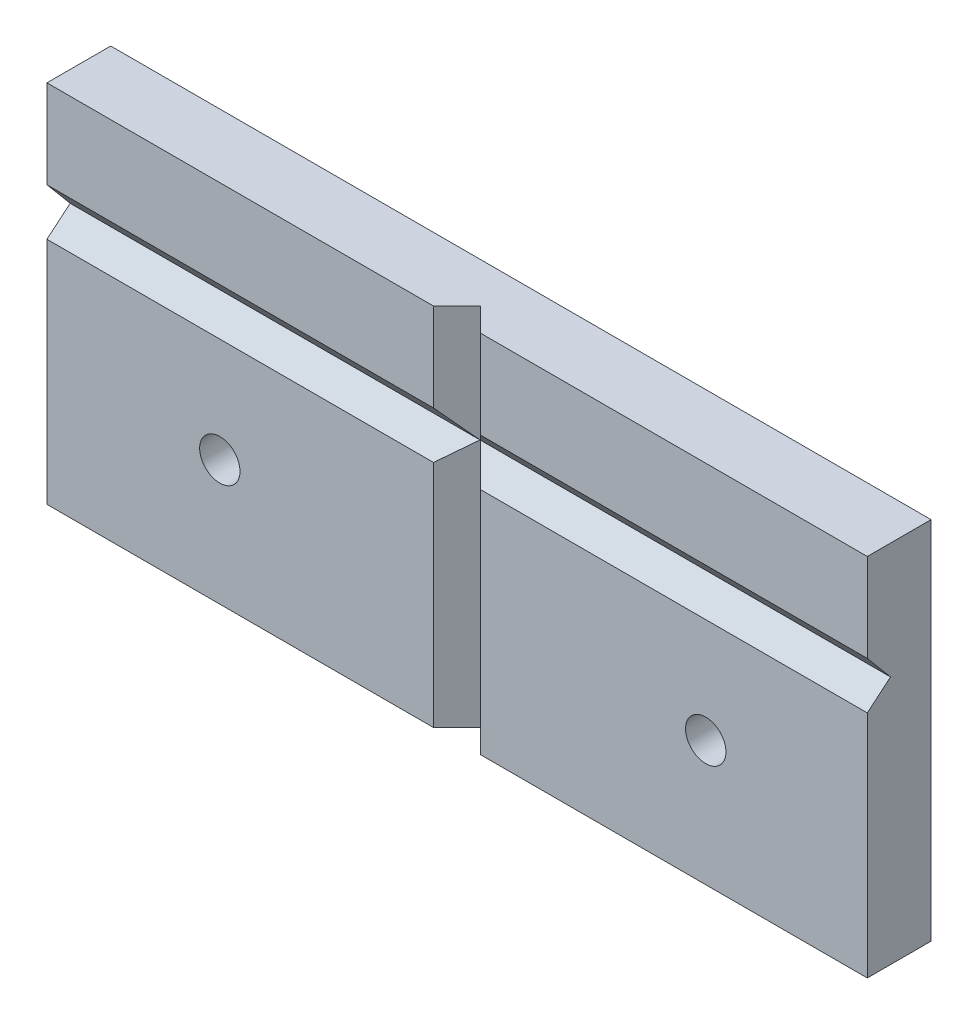
SolidWorks part; units mm, degrees
ref_plane "Front Plane" through (0, 0, 0) normal (0, 0, 1) x (1, 0, 0)
ref_plane "Top Plane" through (0, 0, 0) normal (0, 1, 0) x (1, 0, 0)
ref_plane "Right Plane" through (0, 0, 0) normal (1, 0, 0) x (0, 0, -1)
sketch "Sketch1" plane through (0, 0, 0) normal (0, 0, 1) x (1, 0, 0)
  line L6 (-101.6, 83.312) -> (-101.6, 38.1)
  line L7 (-101.6, 38.1) -> (-69.85, 38.1)
  line L8 (-69.85, 38.1) -> (-31.75, 38.1)
  line L9 (-31.75, 38.1) -> (0, 38.1)
  line L10 (0, 38.1) -> (0, 83.312)
  line L11 (0, 83.312) -> (-101.6, 83.312)
  line L12 (-101.6, 83.312) -> (-101.6, 38.1)
  line L13 (-101.6, 38.1) -> (-69.85, 38.1)
  line L14 (-69.85, 38.1) -> (-31.75, 38.1)
  line L15 (-31.75, 38.1) -> (0, 38.1)
  line L16 (0, 38.1) -> (0, 83.312)
  line L17 (0, 83.312) -> (-101.6, 83.312)
  dimension "D1" = 0
extrude "Boss-Extrude1" add sketch "Sketch1" along normal blind 7.8994
sketch "Sketch2" plane through (-101.6, 0, 0) normal (-1, 0, 0) x (0, 0, 1)
  line L0 (7.8994, 72.3762) -> (5.0225, 68.9498)
  line L1 (7.8994, 83.312) -> (7.8994, 38.1) construction
  line L2 (5.0225, 68.9498) -> (7.8994, 66.5342)
  dimension "D1" = 5.842
extrude "Cut-Extrude1" cut sketch "Sketch2" against normal through all and the other way through all
sketch "Sketch3" plane through (0, 83.312, 0) normal (0, 1, 0) x (1, 0, 0)
  line L0 (-47.879, -7.8994) -> (-50.8, -4.9784)
  line L1 (0, -7.8994) -> (-101.6, -7.8994) construction
  line L2 (-50.8, -4.9784) -> (-53.721, -7.8994)
  line L3 (-50.8, -7.8994) -> (-50.8, 0) construction
  line L4 (0, 0) -> (-101.6, 0) construction
  dimension "D1" = 5.842
extrude "Cut-Extrude2" cut sketch "Sketch3" against normal through all and the other way through all
hole_wizard "M6x1.0 Tapped Hole1" positions "Sketch4" profile "Sketch5" tap size "M6x1.0" standard "ANSI Metric" end condition through all
sketch "Sketch4" plane through (-50.8, 0, 0) normal (0, 0, -1) x (-1, 0, 0)
  line L0 (0, 38.1) -> (0, 74.5807) construction
  line L3 (-50.8, 53.5862) -> (50.8, 53.5862) construction
  point P0 (-30.7952, 53.5862)
  point P2 (29.3872, 53.5862)
sketch "Sketch5" plane through (-20.0048, 53.5862, 0) normal (1, 0, 0) x (0, 1, 0)
  line L0 (0, 0) -> (0, 7.8994)
  line L1 (0, 7.8994) -> (2.5, 7.8994)
  line L2 (2.5, 7.8994) -> (2.5, 0)
  line L3 (2.5, 0) -> (0, 0)
  line L4 (0, -6.35) -> (0, 107.95) construction
  dimension "Thru Tap Drill Dia." = 5
  dimension "Thru Tap Drill Depth" = 7.8994
cosmetic thread "Hole Thread1" parameters "D1"=7.8994, "D2"=6
cosmetic thread "Hole Thread2" parameters "D1"=7.8994, "D2"=6
